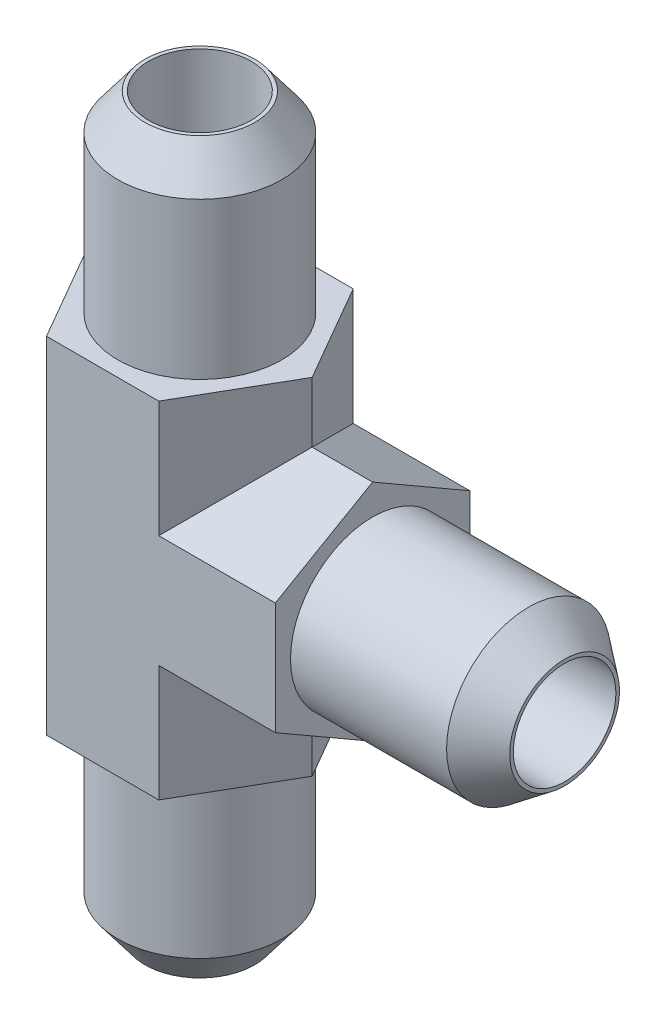
SolidWorks part; units mm, degrees
ref_plane "Front Plane" through (0, 0, 0) normal (0, 0, 1) x (1, 0, 0)
ref_plane "Top Plane" through (0, 0, 0) normal (0, 1, 0) x (1, 0, 0)
ref_plane "Right Plane" through (0, 0, 0) normal (1, 0, 0) x (0, 0, -1)
sketch "Sketch1" plane through (0, 0, 0) normal (0, 1, 0) x (1, 0, 0)
  line L1 (-8.2562, 0) -> (-4.1281, -7.1501)
  line L2 (-4.1281, -7.1501) -> (4.1281, -7.1501)
  line L3 (4.1281, -7.1501) -> (8.2562, 0)
  line L4 (8.2562, 0) -> (4.1281, 7.1501)
  line L5 (4.1281, 7.1501) -> (-4.1281, 7.1501)
  line L6 (-4.1281, 7.1501) -> (-8.2562, 0)
  circle A0 centre (0, 0) radius 7.1501 construction
  dimension "D1" = 14.3002
extrude "Boss-Extrude1" add sketch "Sketch1" along normal mid plane 25.4
sketch "Sketch2" plane through (0, 0, 0) normal (1, 0, 0) x (0, 0, -1)
  line L0 (-7.1501, 12.7) -> (-7.1501, -12.7) construction
  line L1 (0, 8.2562) -> (-7.1501, 4.1281)
  line L2 (-7.1501, 4.1281) -> (-7.1501, -4.1281)
  line L3 (-7.1501, -4.1281) -> (0, -8.2562)
  line L4 (0, -8.2562) -> (7.1501, -4.1281)
  line L5 (7.1501, -4.1281) -> (7.1501, 4.1281)
  line L6 (7.1501, 4.1281) -> (0, 8.2562)
  circle A0 centre (0, 0) radius 7.1501 construction
extrude "Boss-Extrude2" add sketch "Sketch2" along normal blind 12.7
sketch "Sketch3" plane through (12.7, 0, 0) normal (1, 0, 0) x (0, 0, -1)
  circle A0 centre (0, 0) radius 6.0325
  dimension "D1" = 12.065
extrude "Boss-Extrude3" add sketch "Sketch3" along normal blind 14.1224
sketch "Sketch4" plane through (26.8224, 0, 0) normal (1, 0, 0) x (0, 0, -1)
  circle A0 centre (0, 0) radius 4.0386
  circle A1 centre (0, 0) radius 11.3639
  dimension "D1" = 8.0772
extrude "Cut-Extrude1" cut sketch "Sketch4" against normal through all draft 37
sketch "Sketch5" plane through (0, -12.7, 0) normal (0, -1, 0) x (1, 0, 0)
  circle A0 centre (0, 0) radius 6.0325
  dimension "D1" = 12.065
extrude "Boss-Extrude4" add sketch "Sketch5" along normal blind 14.1224
sketch "Sketch6" plane through (0, -26.8224, 0) normal (0, -1, 0) x (1, 0, 0)
  circle A0 centre (0, 0) radius 4.0386
  circle A1 centre (0, 0) radius 16.7971
  dimension "D1" = 8.0772
extrude "Cut-Extrude2" cut sketch "Sketch6" against normal through all draft 37
mirror "Mirror1" about plane through (0, 0, 0) normal (0, 1, 0) of "Boss-Extrude4", "Cut-Extrude2"
sketch "Sketch7" plane through (0, -26.8224, 0) normal (0, -1, 0) x (1, 0, 0)
  circle A0 centre (0, 0) radius 3.7719
  dimension "D1" = 7.5438
extrude "Cut-Extrude3" cut sketch "Sketch7" against normal through all
sketch "Sketch8" plane through (26.8224, 0, 0) normal (1, 0, 0) x (0, 0, -1)
  circle A0 centre (0, 0) radius 3.7719
  dimension "D1" = 7.5438
extrude "Cut-Extrude4" cut sketch "Sketch8" against normal up to next
